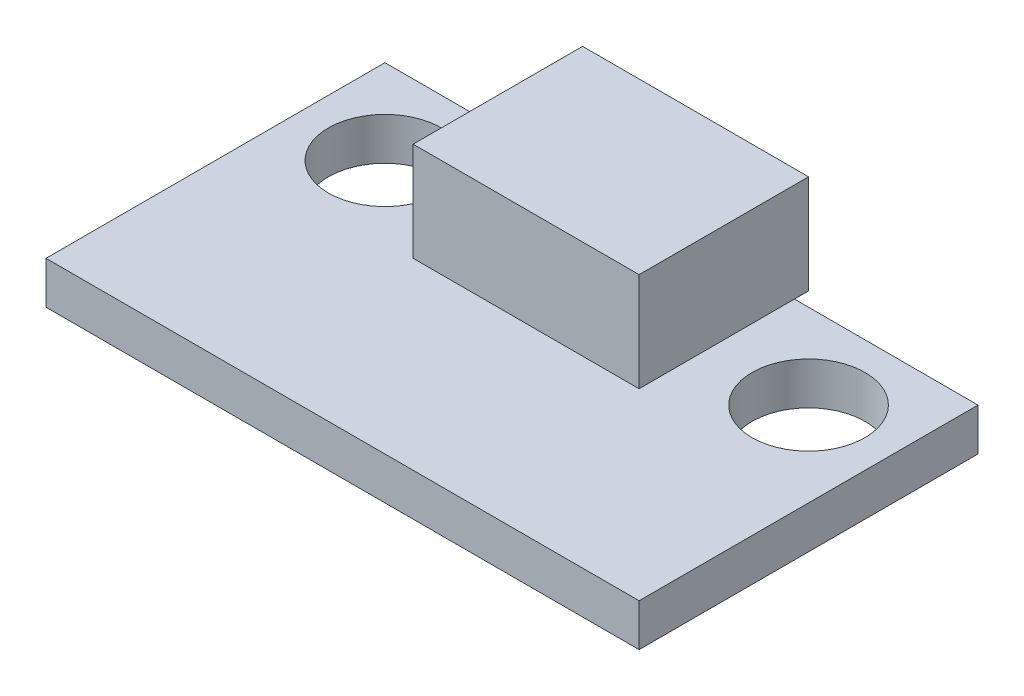
SolidWorks part; units mm, degrees
ref_plane "Front Plane" through (0, 0, 0) normal (0, 0, 1) x (1, 0, 0)
ref_plane "Top Plane" through (0, 0, 0) normal (0, 1, 0) x (1, 0, 0)
ref_plane "Right Plane" through (0, 0, 0) normal (1, 0, 0) x (0, 0, -1)
sketch "Sketch1" plane through (0, 0, 0) normal (0, 1, 0) x (1, 0, 0)
  line L1 (-10.5, 6) -> (10.5, 6)
  line L2 (-10.5, 6) -> (-10.5, -6)
  line L3 (-10.5, -6) -> (10.5, -6)
  line L4 (10.5, 6) -> (10.5, -6)
  line L5 (-10.5, 6) -> (10.5, -6) construction
  line L6 (-10.5, -6) -> (10.5, 6) construction
  point P0 (0, 0)
  dimension "D1" = 12
  dimension "D2" = 21
extrude "Boss-Extrude1" add sketch "Sketch1" along normal blind 1.5
sketch "Sketch2" plane through (0, 1.5, 0) normal (0, 1, 0) x (1, 0, 0)
  line L0 (10.5, 6) -> (-10.5, 6) construction
  line L1 (10.5, -6) -> (10.5, 6) construction
  line L2 (-10.5, 6) -> (-10.5, -6) construction
  circle A0 centre (-7.5, 3) radius 2
  circle A1 centre (7.5, 3) radius 2
  dimension "D1" = 4
  dimension "D2" = 4
  dimension "D6" = 3
  dimension "D3" = 3
  dimension "D4" = 3
  dimension "D5" = 3
extrude "Cut-Extrude1" cut sketch "Sketch2" against normal blind 1.5
sketch "Sketch3" plane through (0, 1.5, 0) normal (0, 1, 0) x (1, 0, 0)
  line L0 (-10.5, -6) -> (10.5, -6) construction
  line L1 (-4, 6.5) -> (4, 6.5)
  line L2 (-4, 6.5) -> (-4, 0.5)
  line L3 (-4, 0.5) -> (4, 0.5)
  line L4 (4, 6.5) -> (4, 0.5)
  line L5 (-4, 6.5) -> (4, 0.5) construction
  line L6 (-4, 0.5) -> (4, 6.5) construction
  point P0 (0, 3.5)
  dimension "D1" = 6
  dimension "D2" = 8
  dimension "D3" = 6.5
  dimension "D4" = 0
extrude "Boss-Extrude2" add sketch "Sketch3" along normal blind 3.5
